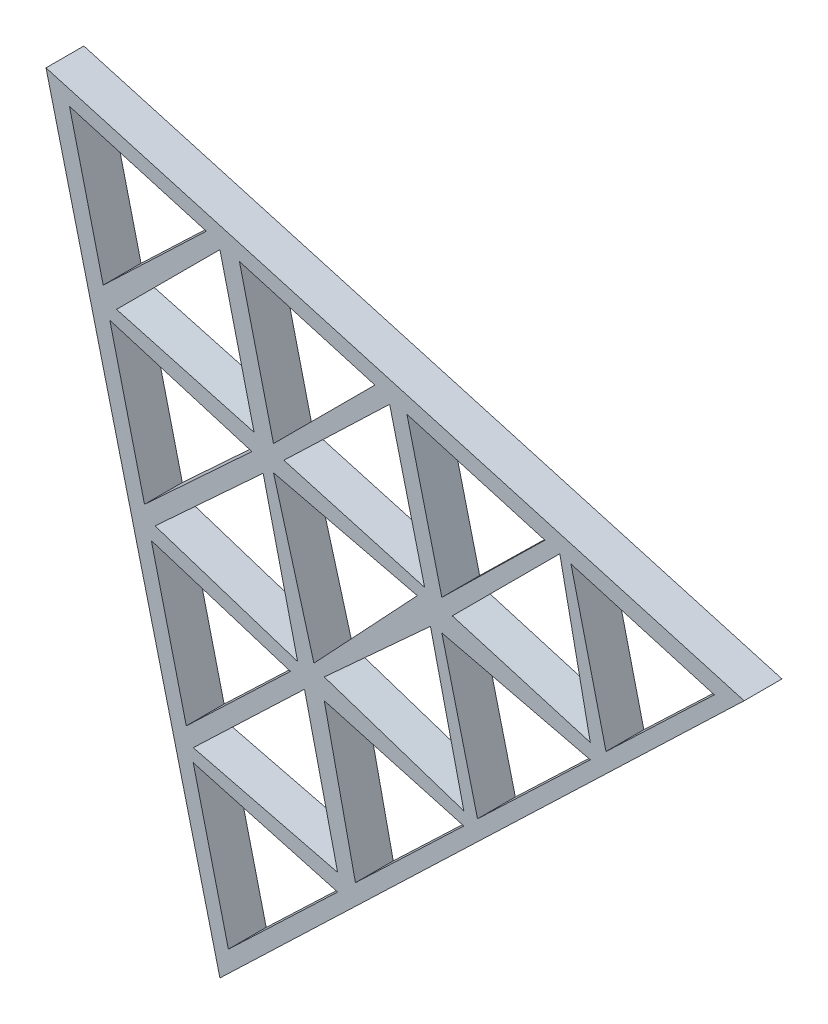
SolidWorks part; units mm, degrees
ref_plane "Plano frontal" through (0, 0, 0) normal (0, 0, 1) x (1, 0, 0)
ref_plane "Plano superior" through (0, 0, 0) normal (0, 1, 0) x (1, 0, 0)
ref_plane "Plano direito" through (0, 0, 0) normal (1, 0, 0) x (0, 0, -1)
sketch "Esboço1" plane through (0, 0, 0) normal (0, 0, 1) x (1, 0, 0)
  line L0 (-126.2385, 94.2854) -> (-80.2759, -91.0556)
  line L1 (-80.2759, -91.0556) -> (58.2789, 41.6741)
  line L2 (58.2789, 41.6741) -> (-126.2385, 94.2854)
  line L3 (-120.0274, 88.5712) -> (-111.1211, 52.1029)
  line L4 (-78.0399, -83.3538) -> (-49.1634, -55.8236)
  line L6 (-83.8752, 78.0786) -> (-111.1211, 52.1029)
  line L7 (-107.605, 48.3228) -> (-80.2759, 75.652)
  line L8 (-80.2759, 75.652) -> (-71.2471, 38.3634)
  line L9 (-71.2471, 38.3634) -> (-107.605, 48.3228)
  line L10 (-75.1207, 75.5377) -> (-66.1145, 38.3425)
  line L11 (-66.1145, 38.3425) -> (-39.3122, 65.1448)
  line L12 (-83.8752, 78.0786) -> (-120.0274, 88.5712)
  line L13 (-109.3762, 44.9581) -> (-71.8287, 33.6645)
  line L14 (-71.8287, 33.6645) -> (-100.2024, 7.3946)
  line L15 (-109.3762, 44.9581) -> (-100.2024, 7.3946)
  line L16 (-30.848, 62.6882) -> (-21.6247, 25.3885)
  line L17 (-21.6247, 25.3885) -> (5.6236, 52.1029)
  line L18 (-39.3122, 65.1448) -> (-75.1207, 75.5377)
  line L19 (-68.8474, 30.1862) -> (-97.4187, 3.8509)
  line L20 (-97.4187, 3.8509) -> (-59.7391, -8.3617)
  line L21 (-59.7391, -8.3617) -> (-68.8474, 30.1862)
  line L22 (-63.3816, 35.9005) -> (-35.4182, 62.6882)
  line L23 (-35.4182, 62.6882) -> (-26.1683, 25.3885)
  line L24 (-26.1683, 25.3885) -> (-63.3816, 35.9005)
  line L25 (-18.8628, 22.5438) -> (9.5552, 50.9618)
  line L26 (9.5552, 50.9618) -> (17.612, 11.8012)
  line L27 (17.612, 11.8012) -> (-18.8628, 22.5438)
  line L28 (5.6236, 52.1029) -> (-30.848, 62.6882)
  line L29 (12.511, 50.1039) -> (21.7683, 11.8012)
  line L30 (12.511, 50.1039) -> (50.4074, 39.1051)
  line L31 (-98.3965, 0) -> (-61.6424, -11.5528)
  line L32 (-61.6424, -11.5528) -> (-89.1666, -37.7937)
  line L33 (-87.3321, -45.3052) -> (-49.1634, -55.8236)
  line L34 (-87.3321, -45.3052) -> (-78.0399, -83.3538)
  line L35 (-98.3965, 0) -> (-89.1666, -37.7937)
  line L36 (-66.1145, 31.6769) -> (-55.4313, -6.5838)
  line L37 (-55.4313, -6.5838) -> (-28.1022, 22.5438)
  line L38 (-28.1022, 22.5438) -> (-66.1145, 31.6769)
  line L39 (-52.6984, -8.3617) -> (-24.6239, 17.267)
  line L40 (-24.6239, 17.267) -> (-15.8134, -20.5754)
  line L41 (-15.8134, -20.5754) -> (-52.6984, -8.3617)
  line L42 (-44.4571, -51.3367) -> (-52.6984, -13.7888)
  line L43 (-52.6984, -13.7888) -> (-15.8134, -24.0283)
  line L44 (-44.4571, -51.3367) -> (-15.8134, -24.0283)
  line L45 (-21.6247, 17.267) -> (-12.1916, -20.5754)
  line L46 (-21.6247, 17.267) -> (17.612, 7.8387)
  line L47 (21.7683, 11.8012) -> (50.4074, 39.1051)
  line L48 (-12.1916, -20.5754) -> (17.612, 7.8387)
  line L49 (-57.9157, -13.7888) -> (-49.1634, -51.3367)
  line L50 (-49.1634, -51.3367) -> (-87.3321, -41.8632)
  line L51 (-87.3321, -41.8632) -> (-57.9157, -13.7888)
extrude "Ressalto-extrusão1" add sketch "Esboço1" along normal blind 10
